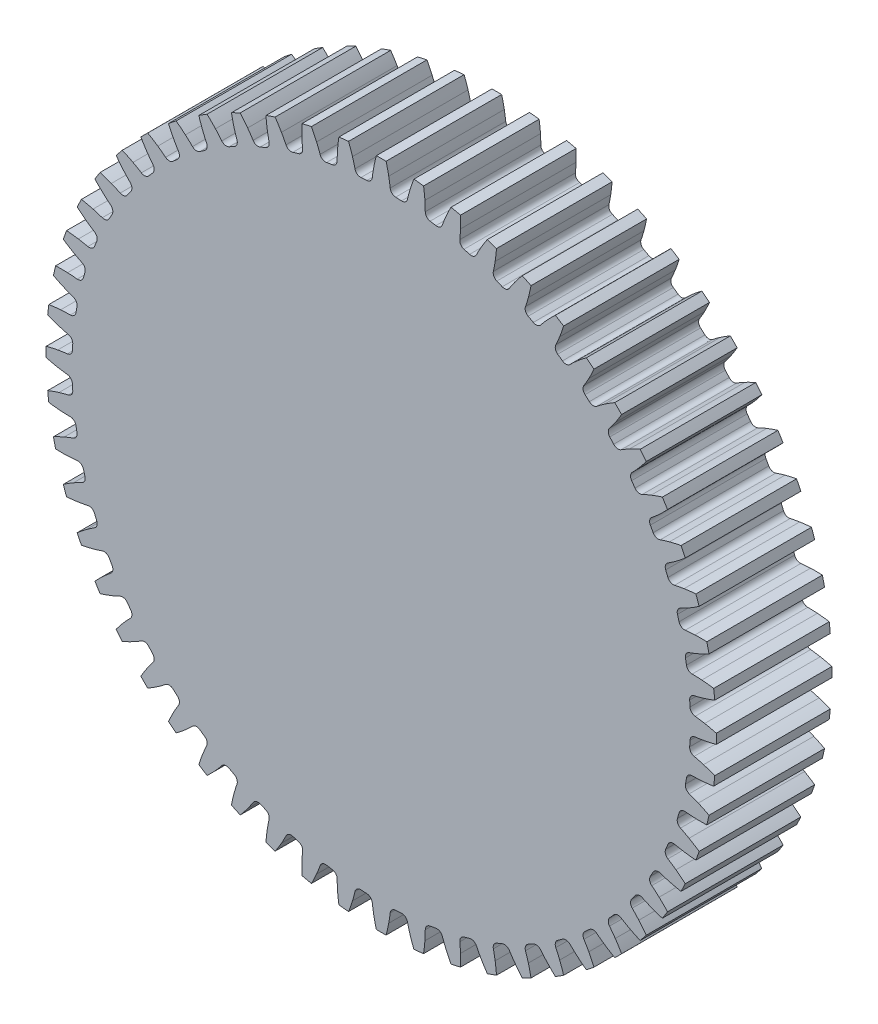
SolidWorks part; units mm, degrees
ref_plane "Front Plane" through (0, 0, 0) normal (0, 0, 1) x (1, 0, 0)
ref_plane "Top Plane" through (0, 0, 0) normal (0, 1, 0) x (1, 0, 0)
ref_plane "Right Plane" through (0, 0, 0) normal (1, 0, 0) x (0, 0, -1)
sketch "Sketch1" plane through (0, 0, 0) normal (0, 0, 1) x (1, 0, 0)
  line L0 (0, 145) -> (0, -145) construction
  circle A0 centre (0, 0) radius 140 construction
  circle A1 centre (0, 0) radius 145 construction
  arc A2 (-6.2373, 133.6045) -> (-8.7609, 133.4628) centre (0, 0) ccw
  arc A3 (-2.1, 144.9848) -> (2.1, 144.9848) centre (0, 0) cw
  arc A4 (2.1, 144.9848) -> (3.25, 139.9623) centre (-59.4844, 128.241) cw
  arc A5 (3.25, 139.9623) -> (3.8697, 135.8214) centre (-53.6651, 129.3283) cw
  arc A6 (3.8697, 135.8214) -> (6.2373, 133.6045) centre (6.3539, 136.1018) ccw
  arc A7 (-2.1, 144.9848) -> (-3.25, 139.9623) centre (59.4844, 128.241) ccw
  arc A8 (-3.25, 139.9623) -> (-3.8697, 135.8214) centre (53.6651, 129.3283) ccw
  arc A9 (-3.8697, 135.8214) -> (-6.2373, 133.6045) centre (-6.3539, 136.1018) cw
  arc A10 (11.3618, 135.4007) -> (8.7609, 133.4628) centre (8.9246, 135.9574) cw
  arc A11 (12.4412, 139.4461) -> (11.3618, 135.4007) centre (67.8078, 122.5065) ccw
  arc A12 (14.1464, 144.3083) -> (12.4412, 139.4461) centre (73.4688, 120.7745) ccw
  arc A13 (14.1464, 144.3083) -> (18.3199, 143.838) centre (0, 0) cw
  arc A14 (18.3199, 143.838) -> (18.9004, 138.7183) centre (-44.7519, 134.0948) cw
  arc A15 (18.9004, 138.7183) -> (19.0525, 134.5341) centre (-38.8475, 134.5237) cw
  arc A16 (19.0525, 134.5341) -> (21.1571, 132.0661) centre (21.5525, 134.5346) ccw
  arc A17 (26.4505, 133.2772) -> (23.6489, 131.6427) centre (24.0909, 134.1033) cw
  arc A18 (27.976, 137.1763) -> (26.4505, 133.2772) centre (81.0978, 114.1441) ccw
  arc A19 (30.2148, 141.817) -> (27.976, 137.1763) centre (86.5293, 111.7892) ccw
  arc A20 (30.2148, 141.817) -> (34.3095, 140.8824) centre (0, 0) cw
  arc A21 (34.3095, 140.8824) -> (34.3131, 135.7299) centre (-29.4567, 138.2622) cw
  arc A22 (34.3131, 135.7299) -> (33.9958, 131.555) centre (-23.5414, 138.0273) cw
  arc A23 (33.9958, 131.555) -> (35.8107, 128.8668) centre (36.4801, 131.2755) ccw
  arc A24 (41.2064, 129.4776) -> (38.2395, 128.1671) centre (38.9542, 130.5627) cw
  arc A25 (43.159, 133.1815) -> (41.2064, 129.4776) centre (93.368, 104.3463) ccw
  arc A26 (45.9033, 137.5423) -> (43.159, 133.1815) centre (98.5016, 101.3981) ccw
  arc A27 (45.9033, 137.5423) -> (49.8676, 136.1551) centre (0, 0) cw
  arc A28 (49.8676, 136.1551) -> (49.2942, 131.0346) centre (-13.791, 140.691) cw
  arc A29 (49.2942, 131.0346) -> (48.5115, 126.9215) centre (-7.9392, 139.7952) cw
  arc A30 (48.5115, 126.9215) -> (50.0141, 124.047) centre (50.9489, 126.3656) ccw
  arc A31 (55.4442, 124.0498) -> (52.3492, 123.0798) centre (53.3277, 125.3803) cw
  arc A32 (57.7992, 127.5118) -> (55.4442, 124.0498) centre (104.464, 93.2363) ccw
  arc A33 (61.0145, 131.5379) -> (57.7992, 127.5118) centre (109.2353, 89.7318) ccw
  arc A34 (61.0145, 131.5379) -> (64.7986, 129.7156) centre (0, 0) cw
  arc A35 (64.7986, 129.7156) -> (63.6555, 124.6915) centre (2.0481, 141.3504) cw
  arc A36 (63.6555, 124.6915) -> (62.4172, 120.6919) centre (7.7628, 139.8051) cw
  arc A37 (62.4172, 120.6919) -> (63.5884, 117.6672) centre (64.777, 119.8666) ccw
  arc A38 (68.9848, 117.0621) -> (65.8006, 116.4446) centre (67.0305, 118.6211) cw
  arc A39 (71.7126, 120.2385) -> (68.9848, 117.0621) centre (114.2463, 80.9538) ccw
  arc A40 (75.3584, 123.8794) -> (71.7126, 120.2385) centre (118.5952, 76.9371) ccw
  arc A41 (75.3584, 123.8794) -> (78.9147, 121.6449) centre (0, 0) cw
  arc A42 (78.9147, 121.6449) -> (77.2163, 116.7803) centre (17.8614, 140.2323) cw
  arc A43 (77.2163, 116.7803) -> (75.5379, 112.9445) centre (23.3672, 138.0569) cw
  arc A44 (75.5379, 112.9445) -> (76.3632, 109.8077) centre (77.7905, 111.8602) ccw
  arc A45 (81.6578, 108.6022) -> (78.4245, 108.3451) centre (79.8904, 110.3702) cw
  arc A46 (84.7241, 111.4533) -> (81.6578, 108.6022) centre (122.5919, 67.6533) ccw
  arc A47 (88.7547, 114.663) -> (84.7241, 111.4533) centre (126.4637, 63.1749) ccw
  arc A48 (88.7547, 114.663) -> (92.0384, 112.0443) centre (0, 0) cw
  arc A49 (92.0384, 112.0443) -> (89.806, 107.4006) centre (33.4502, 137.3507) cw
  arc A50 (89.806, 107.4006) -> (87.7087, 103.7767) centre (38.6778, 134.5725) cw
  arc A51 (87.7087, 103.7767) -> (88.1776, 100.5673) centre (89.8257, 102.4471) ccw
  arc A52 (93.304, 98.7765) -> (90.0622, 98.8831) centre (91.7456, 100.7314) cw
  arc A53 (96.6702, 101.2664) -> (93.304, 98.7765) centre (129.3958, 53.5019) ccw
  arc A54 (101.0348, 104.0047) -> (96.6702, 101.2664) centre (132.7419, 48.6182) ccw
  arc A55 (101.0348, 104.0047) -> (104.0047, 101.0348) centre (0, 0) cw
  arc A56 (104.0047, 101.0348) -> (101.2664, 96.6702) centre (48.6182, 132.7419) cw
  arc A57 (101.2664, 96.6702) -> (98.7765, 93.304) centre (53.5019, 129.3958) cw
  arc A58 (98.7765, 93.304) -> (98.8831, 90.0622) centre (100.7314, 91.7456) ccw
  arc A59 (103.7767, 87.7087) -> (100.5673, 88.1776) centre (102.4471, 89.8257) cw
  arc A60 (107.4006, 89.806) -> (103.7767, 87.7087) centre (134.5725, 38.6778) ccw
  arc A61 (112.0443, 92.0384) -> (107.4006, 89.806) centre (137.3507, 33.4502) ccw
  arc A62 (112.0443, 92.0384) -> (114.663, 88.7547) centre (0, 0) cw
  arc A63 (114.663, 88.7547) -> (111.4533, 84.7241) centre (63.1749, 126.4637) cw
  arc A64 (111.4533, 84.7241) -> (108.6022, 81.6578) centre (67.6533, 122.5919) cw
  arc A65 (108.6022, 81.6578) -> (108.3451, 78.4245) centre (110.3702, 79.8904) ccw
  arc A66 (112.9445, 75.5379) -> (109.8077, 76.3632) centre (111.8602, 77.7905) cw
  arc A67 (116.7803, 77.2163) -> (112.9445, 75.5379) centre (138.0569, 23.3672) ccw
  arc A68 (121.6449, 78.9147) -> (116.7803, 77.2163) centre (140.2323, 17.8614) ccw
  arc A69 (121.6449, 78.9147) -> (123.8794, 75.3584) centre (0, 0) cw
  arc A70 (123.8794, 75.3584) -> (120.2385, 71.7126) centre (76.9371, 118.5952) cw
  arc A71 (120.2385, 71.7126) -> (117.0621, 68.9848) centre (80.9538, 114.2463) cw
  arc A72 (117.0621, 68.9848) -> (116.4446, 65.8006) centre (118.6211, 67.0305) ccw
  arc A73 (120.6919, 62.4172) -> (117.6672, 63.5884) centre (119.8666, 64.777) cw
  arc A74 (124.6915, 63.6555) -> (120.6919, 62.4172) centre (139.8051, 7.7628) ccw
  arc A75 (129.7156, 64.7986) -> (124.6915, 63.6555) centre (141.3504, 2.0481) ccw
  arc A76 (129.7156, 64.7986) -> (131.5379, 61.0145) centre (0, 0) cw
  arc A77 (131.5379, 61.0145) -> (127.5118, 57.7992) centre (89.7318, 109.2353) cw
  arc A78 (127.5118, 57.7992) -> (124.0498, 55.4442) centre (93.2363, 104.464) cw
  arc A79 (124.0498, 55.4442) -> (123.0798, 52.3492) centre (125.3803, 53.3277) ccw
  arc A80 (126.9215, 48.5115) -> (124.047, 50.0141) centre (126.3656, 50.9489) cw
  arc A81 (131.0346, 49.2942) -> (126.9215, 48.5115) centre (139.7952, -7.9392) ccw
  arc A82 (136.1551, 49.8676) -> (131.0346, 49.2942) centre (140.691, -13.791) ccw
  arc A83 (136.1551, 49.8676) -> (137.5423, 45.9033) centre (0, 0) cw
  arc A84 (137.5423, 45.9033) -> (133.1815, 43.159) centre (101.3981, 98.5016) cw
  arc A85 (133.1815, 43.159) -> (129.4776, 41.2064) centre (104.3463, 93.368) cw
  arc A86 (129.4776, 41.2064) -> (128.1671, 38.2395) centre (130.5627, 38.9542) ccw
  arc A87 (131.555, 33.9958) -> (128.8668, 35.8107) centre (131.2755, 36.4801) cw
  arc A88 (135.7299, 34.3131) -> (131.555, 33.9958) centre (138.0273, -23.5414) ccw
  arc A89 (140.8824, 34.3095) -> (135.7299, 34.3131) centre (138.2622, -29.4567) ccw
  arc A90 (140.8824, 34.3095) -> (141.817, 30.2148) centre (0, 0) cw
  arc A91 (141.817, 30.2148) -> (137.1763, 27.976) centre (111.7892, 86.5293) cw
  arc A92 (137.1763, 27.976) -> (133.2772, 26.4505) centre (114.1441, 81.0978) cw
  arc A93 (133.2772, 26.4505) -> (131.6427, 23.6489) centre (134.1033, 24.0909) ccw
  arc A94 (134.5341, 19.0525) -> (132.0661, 21.1571) centre (134.5346, 21.5525) cw
  arc A95 (138.7183, 18.9004) -> (134.5341, 19.0525) centre (134.5237, -38.8475) ccw
  arc A96 (143.838, 18.3199) -> (138.7183, 18.9004) centre (134.0948, -44.7519) ccw
  arc A97 (143.838, 18.3199) -> (144.3083, 14.1464) centre (0, 0) cw
  arc A98 (144.3083, 14.1464) -> (139.4461, 12.4412) centre (120.7745, 73.4688) cw
  arc A99 (139.4461, 12.4412) -> (135.4007, 11.3618) centre (122.5065, 67.8078) cw
  arc A100 (135.4007, 11.3618) -> (133.4628, 8.7609) centre (135.9574, 8.9246) ccw
  arc A101 (135.8214, 3.8697) -> (133.6045, 6.2373) centre (136.1018, 6.3539) cw
  arc A102 (139.9623, 3.25) -> (135.8214, 3.8697) centre (129.3283, -53.6651) ccw
  arc A103 (144.9848, 2.1) -> (139.9623, 3.25) centre (128.241, -59.4844) ccw
  arc A104 (144.9848, 2.1) -> (144.9848, -2.1) centre (0, 0) cw
  arc A105 (144.9848, -2.1) -> (139.9623, -3.25) centre (128.241, 59.4844) cw
  arc A106 (139.9623, -3.25) -> (135.8214, -3.8697) centre (129.3283, 53.6651) cw
  arc A107 (135.8214, -3.8697) -> (133.6045, -6.2373) centre (136.1018, -6.3539) ccw
  arc A108 (135.4007, -11.3618) -> (133.4628, -8.7609) centre (135.9574, -8.9246) cw
  arc A109 (139.4461, -12.4412) -> (135.4007, -11.3618) centre (122.5065, -67.8078) ccw
  arc A110 (144.3083, -14.1464) -> (139.4461, -12.4412) centre (120.7745, -73.4688) ccw
  arc A111 (144.3083, -14.1464) -> (143.838, -18.3199) centre (0, 0) cw
  arc A112 (143.838, -18.3199) -> (138.7183, -18.9004) centre (134.0948, 44.7519) cw
  arc A113 (138.7183, -18.9004) -> (134.5341, -19.0525) centre (134.5237, 38.8475) cw
  arc A114 (134.5341, -19.0525) -> (132.0661, -21.1571) centre (134.5346, -21.5525) ccw
  arc A115 (133.2772, -26.4505) -> (131.6427, -23.6489) centre (134.1033, -24.0909) cw
  arc A116 (137.1763, -27.976) -> (133.2772, -26.4505) centre (114.1441, -81.0978) ccw
  arc A117 (141.817, -30.2148) -> (137.1763, -27.976) centre (111.7892, -86.5293) ccw
  arc A118 (141.817, -30.2148) -> (140.8824, -34.3095) centre (0, 0) cw
  arc A119 (140.8824, -34.3095) -> (135.7299, -34.3131) centre (138.2622, 29.4567) cw
  arc A120 (135.7299, -34.3131) -> (131.555, -33.9958) centre (138.0273, 23.5414) cw
  arc A121 (131.555, -33.9958) -> (128.8668, -35.8107) centre (131.2755, -36.4801) ccw
  arc A122 (129.4776, -41.2064) -> (128.1671, -38.2395) centre (130.5627, -38.9542) cw
  arc A123 (133.1815, -43.159) -> (129.4776, -41.2064) centre (104.3463, -93.368) ccw
  arc A124 (137.5423, -45.9033) -> (133.1815, -43.159) centre (101.3981, -98.5016) ccw
  arc A125 (137.5423, -45.9033) -> (136.1551, -49.8676) centre (0, 0) cw
  arc A126 (136.1551, -49.8676) -> (131.0346, -49.2942) centre (140.691, 13.791) cw
  arc A127 (131.0346, -49.2942) -> (126.9215, -48.5115) centre (139.7952, 7.9392) cw
  arc A128 (126.9215, -48.5115) -> (124.047, -50.0141) centre (126.3656, -50.9489) ccw
  arc A129 (124.0498, -55.4442) -> (123.0798, -52.3492) centre (125.3803, -53.3277) cw
  arc A130 (127.5118, -57.7992) -> (124.0498, -55.4442) centre (93.2363, -104.464) ccw
  arc A131 (131.5379, -61.0145) -> (127.5118, -57.7992) centre (89.7318, -109.2353) ccw
  arc A132 (131.5379, -61.0145) -> (129.7156, -64.7986) centre (0, 0) cw
  arc A133 (129.7156, -64.7986) -> (124.6915, -63.6555) centre (141.3504, -2.0481) cw
  arc A134 (124.6915, -63.6555) -> (120.6919, -62.4172) centre (139.8051, -7.7628) cw
  arc A135 (120.6919, -62.4172) -> (117.6672, -63.5884) centre (119.8666, -64.777) ccw
  arc A136 (117.0621, -68.9848) -> (116.4446, -65.8006) centre (118.6211, -67.0305) cw
  arc A137 (120.2385, -71.7126) -> (117.0621, -68.9848) centre (80.9538, -114.2463) ccw
  arc A138 (123.8794, -75.3584) -> (120.2385, -71.7126) centre (76.9371, -118.5952) ccw
  arc A139 (123.8794, -75.3584) -> (121.6449, -78.9147) centre (0, 0) cw
  arc A140 (121.6449, -78.9147) -> (116.7803, -77.2163) centre (140.2323, -17.8614) cw
  arc A141 (116.7803, -77.2163) -> (112.9445, -75.5379) centre (138.0569, -23.3672) cw
  arc A142 (112.9445, -75.5379) -> (109.8077, -76.3632) centre (111.8602, -77.7905) ccw
  arc A143 (108.6022, -81.6578) -> (108.3451, -78.4245) centre (110.3702, -79.8904) cw
  arc A144 (111.4533, -84.7241) -> (108.6022, -81.6578) centre (67.6533, -122.5919) ccw
  arc A145 (114.663, -88.7547) -> (111.4533, -84.7241) centre (63.1749, -126.4637) ccw
  arc A146 (114.663, -88.7547) -> (112.0443, -92.0384) centre (0, 0) cw
  arc A147 (112.0443, -92.0384) -> (107.4006, -89.806) centre (137.3507, -33.4502) cw
  arc A148 (107.4006, -89.806) -> (103.7767, -87.7087) centre (134.5725, -38.6778) cw
  arc A149 (103.7767, -87.7087) -> (100.5673, -88.1776) centre (102.4471, -89.8257) ccw
  arc A150 (98.7765, -93.304) -> (98.8831, -90.0622) centre (100.7314, -91.7456) cw
  arc A151 (101.2664, -96.6702) -> (98.7765, -93.304) centre (53.5019, -129.3958) ccw
  arc A152 (104.0047, -101.0348) -> (101.2664, -96.6702) centre (48.6182, -132.7419) ccw
  arc A153 (104.0047, -101.0348) -> (101.0348, -104.0047) centre (0, 0) cw
  arc A154 (101.0348, -104.0047) -> (96.6702, -101.2664) centre (132.7419, -48.6182) cw
  arc A155 (96.6702, -101.2664) -> (93.304, -98.7765) centre (129.3958, -53.5019) cw
  arc A156 (93.304, -98.7765) -> (90.0622, -98.8831) centre (91.7456, -100.7314) ccw
  arc A157 (87.7087, -103.7767) -> (88.1776, -100.5673) centre (89.8257, -102.4471) cw
  arc A158 (89.806, -107.4006) -> (87.7087, -103.7767) centre (38.6778, -134.5725) ccw
  arc A159 (92.0384, -112.0443) -> (89.806, -107.4006) centre (33.4502, -137.3507) ccw
  arc A160 (92.0384, -112.0443) -> (88.7547, -114.663) centre (0, 0) cw
  arc A161 (88.7547, -114.663) -> (84.7241, -111.4533) centre (126.4637, -63.1749) cw
  arc A162 (84.7241, -111.4533) -> (81.6578, -108.6022) centre (122.5919, -67.6533) cw
  arc A163 (81.6578, -108.6022) -> (78.4245, -108.3451) centre (79.8904, -110.3702) ccw
  arc A164 (75.5379, -112.9445) -> (76.3632, -109.8077) centre (77.7905, -111.8602) cw
  arc A165 (77.2163, -116.7803) -> (75.5379, -112.9445) centre (23.3672, -138.0569) ccw
  arc A166 (78.9147, -121.6449) -> (77.2163, -116.7803) centre (17.8614, -140.2323) ccw
  arc A167 (78.9147, -121.6449) -> (75.3584, -123.8794) centre (0, 0) cw
  arc A168 (75.3584, -123.8794) -> (71.7126, -120.2385) centre (118.5952, -76.9371) cw
  arc A169 (71.7126, -120.2385) -> (68.9848, -117.0621) centre (114.2463, -80.9538) cw
  arc A170 (68.9848, -117.0621) -> (65.8006, -116.4446) centre (67.0305, -118.6211) ccw
  arc A171 (62.4172, -120.6919) -> (63.5884, -117.6672) centre (64.777, -119.8666) cw
  arc A172 (63.6555, -124.6915) -> (62.4172, -120.6919) centre (7.7628, -139.8051) ccw
  arc A173 (64.7986, -129.7156) -> (63.6555, -124.6915) centre (2.0481, -141.3504) ccw
  arc A174 (64.7986, -129.7156) -> (61.0145, -131.5379) centre (0, 0) cw
  arc A175 (61.0145, -131.5379) -> (57.7992, -127.5118) centre (109.2353, -89.7318) cw
  arc A176 (57.7992, -127.5118) -> (55.4442, -124.0498) centre (104.464, -93.2363) cw
  arc A177 (55.4442, -124.0498) -> (52.3492, -123.0798) centre (53.3277, -125.3803) ccw
  arc A178 (48.5115, -126.9215) -> (50.0141, -124.047) centre (50.9489, -126.3656) cw
  arc A179 (49.2942, -131.0346) -> (48.5115, -126.9215) centre (-7.9392, -139.7952) ccw
  arc A180 (49.8676, -136.1551) -> (49.2942, -131.0346) centre (-13.791, -140.691) ccw
  arc A181 (49.8676, -136.1551) -> (45.9033, -137.5423) centre (0, 0) cw
  arc A182 (45.9033, -137.5423) -> (43.159, -133.1815) centre (98.5016, -101.3981) cw
  arc A183 (43.159, -133.1815) -> (41.2064, -129.4776) centre (93.368, -104.3463) cw
  arc A184 (41.2064, -129.4776) -> (38.2395, -128.1671) centre (38.9542, -130.5627) ccw
  arc A185 (33.9958, -131.555) -> (35.8107, -128.8668) centre (36.4801, -131.2755) cw
  arc A186 (34.3131, -135.7299) -> (33.9958, -131.555) centre (-23.5414, -138.0273) ccw
  arc A187 (34.3095, -140.8824) -> (34.3131, -135.7299) centre (-29.4567, -138.2622) ccw
  arc A188 (34.3095, -140.8824) -> (30.2148, -141.817) centre (0, 0) cw
  arc A189 (30.2148, -141.817) -> (27.976, -137.1763) centre (86.5293, -111.7892) cw
  arc A190 (27.976, -137.1763) -> (26.4505, -133.2772) centre (81.0978, -114.1441) cw
  arc A191 (26.4505, -133.2772) -> (23.6489, -131.6427) centre (24.0909, -134.1033) ccw
  arc A192 (19.0525, -134.5341) -> (21.1571, -132.0661) centre (21.5525, -134.5346) cw
  arc A193 (18.9004, -138.7183) -> (19.0525, -134.5341) centre (-38.8475, -134.5237) ccw
  arc A194 (18.3199, -143.838) -> (18.9004, -138.7183) centre (-44.7519, -134.0948) ccw
  arc A195 (18.3199, -143.838) -> (14.1464, -144.3083) centre (0, 0) cw
  arc A196 (14.1464, -144.3083) -> (12.4412, -139.4461) centre (73.4688, -120.7745) cw
  arc A197 (12.4412, -139.4461) -> (11.3618, -135.4007) centre (67.8078, -122.5065) cw
  arc A198 (11.3618, -135.4007) -> (8.7609, -133.4628) centre (8.9246, -135.9574) ccw
  arc A199 (3.8697, -135.8214) -> (6.2373, -133.6045) centre (6.3539, -136.1018) cw
  arc A200 (3.25, -139.9623) -> (3.8697, -135.8214) centre (-53.6651, -129.3283) ccw
  arc A201 (2.1, -144.9848) -> (3.25, -139.9623) centre (-59.4844, -128.241) ccw
  arc A202 (2.1, -144.9848) -> (-2.1, -144.9848) centre (0, 0) cw
  arc A203 (-2.1, -144.9848) -> (-3.25, -139.9623) centre (59.4844, -128.241) cw
  arc A204 (-3.25, -139.9623) -> (-3.8697, -135.8214) centre (53.6651, -129.3283) cw
  arc A205 (-3.8697, -135.8214) -> (-6.2373, -133.6045) centre (-6.3539, -136.1018) ccw
  arc A206 (-11.3618, -135.4007) -> (-8.7609, -133.4628) centre (-8.9246, -135.9574) cw
  arc A207 (-12.4412, -139.4461) -> (-11.3618, -135.4007) centre (-67.8078, -122.5065) ccw
  arc A208 (-14.1464, -144.3083) -> (-12.4412, -139.4461) centre (-73.4688, -120.7745) ccw
  arc A209 (-14.1464, -144.3083) -> (-18.3199, -143.838) centre (0, 0) cw
  arc A210 (-18.3199, -143.838) -> (-18.9004, -138.7183) centre (44.7519, -134.0948) cw
  arc A211 (-18.9004, -138.7183) -> (-19.0525, -134.5341) centre (38.8475, -134.5237) cw
  arc A212 (-19.0525, -134.5341) -> (-21.1571, -132.0661) centre (-21.5525, -134.5346) ccw
  arc A213 (-26.4505, -133.2772) -> (-23.6489, -131.6427) centre (-24.0909, -134.1033) cw
  arc A214 (-27.976, -137.1763) -> (-26.4505, -133.2772) centre (-81.0978, -114.1441) ccw
  arc A215 (-30.2148, -141.817) -> (-27.976, -137.1763) centre (-86.5293, -111.7892) ccw
  arc A216 (-30.2148, -141.817) -> (-34.3095, -140.8824) centre (0, 0) cw
  arc A217 (-34.3095, -140.8824) -> (-34.3131, -135.7299) centre (29.4567, -138.2622) cw
  arc A218 (-34.3131, -135.7299) -> (-33.9958, -131.555) centre (23.5414, -138.0273) cw
  arc A219 (-33.9958, -131.555) -> (-35.8107, -128.8668) centre (-36.4801, -131.2755) ccw
  arc A220 (-41.2064, -129.4776) -> (-38.2395, -128.1671) centre (-38.9542, -130.5627) cw
  arc A221 (-43.159, -133.1815) -> (-41.2064, -129.4776) centre (-93.368, -104.3463) ccw
  arc A222 (-45.9033, -137.5423) -> (-43.159, -133.1815) centre (-98.5016, -101.3981) ccw
  arc A223 (-45.9033, -137.5423) -> (-49.8676, -136.1551) centre (0, 0) cw
  arc A224 (-49.8676, -136.1551) -> (-49.2942, -131.0346) centre (13.791, -140.691) cw
  arc A225 (-49.2942, -131.0346) -> (-48.5115, -126.9215) centre (7.9392, -139.7952) cw
  arc A226 (-48.5115, -126.9215) -> (-50.0141, -124.047) centre (-50.9489, -126.3656) ccw
  arc A227 (-55.4442, -124.0498) -> (-52.3492, -123.0798) centre (-53.3277, -125.3803) cw
  arc A228 (-57.7992, -127.5118) -> (-55.4442, -124.0498) centre (-104.464, -93.2363) ccw
  arc A229 (-61.0145, -131.5379) -> (-57.7992, -127.5118) centre (-109.2353, -89.7318) ccw
  arc A230 (-61.0145, -131.5379) -> (-64.7986, -129.7156) centre (0, 0) cw
  arc A231 (-64.7986, -129.7156) -> (-63.6555, -124.6915) centre (-2.0481, -141.3504) cw
  arc A232 (-63.6555, -124.6915) -> (-62.4172, -120.6919) centre (-7.7628, -139.8051) cw
  arc A233 (-62.4172, -120.6919) -> (-63.5884, -117.6672) centre (-64.777, -119.8666) ccw
  arc A234 (-68.9848, -117.0621) -> (-65.8006, -116.4446) centre (-67.0305, -118.6211) cw
  arc A235 (-71.7126, -120.2385) -> (-68.9848, -117.0621) centre (-114.2463, -80.9538) ccw
  arc A236 (-75.3584, -123.8794) -> (-71.7126, -120.2385) centre (-118.5952, -76.9371) ccw
  arc A237 (-75.3584, -123.8794) -> (-78.9147, -121.6449) centre (0, 0) cw
  arc A238 (-78.9147, -121.6449) -> (-77.2163, -116.7803) centre (-17.8614, -140.2323) cw
  arc A239 (-77.2163, -116.7803) -> (-75.5379, -112.9445) centre (-23.3672, -138.0569) cw
  arc A240 (-75.5379, -112.9445) -> (-76.3632, -109.8077) centre (-77.7905, -111.8602) ccw
  arc A241 (-81.6578, -108.6022) -> (-78.4245, -108.3451) centre (-79.8904, -110.3702) cw
  arc A242 (-84.7241, -111.4533) -> (-81.6578, -108.6022) centre (-122.5919, -67.6533) ccw
  arc A243 (-88.7547, -114.663) -> (-84.7241, -111.4533) centre (-126.4637, -63.1749) ccw
  arc A244 (-88.7547, -114.663) -> (-92.0384, -112.0443) centre (0, 0) cw
  arc A245 (-92.0384, -112.0443) -> (-89.806, -107.4006) centre (-33.4502, -137.3507) cw
  arc A246 (-89.806, -107.4006) -> (-87.7087, -103.7767) centre (-38.6778, -134.5725) cw
  arc A247 (-87.7087, -103.7767) -> (-88.1776, -100.5673) centre (-89.8257, -102.4471) ccw
  arc A248 (-93.304, -98.7765) -> (-90.0622, -98.8831) centre (-91.7456, -100.7314) cw
  arc A249 (-96.6702, -101.2664) -> (-93.304, -98.7765) centre (-129.3958, -53.5019) ccw
  arc A250 (-101.0348, -104.0047) -> (-96.6702, -101.2664) centre (-132.7419, -48.6182) ccw
  arc A251 (-101.0348, -104.0047) -> (-104.0047, -101.0348) centre (0, 0) cw
  arc A252 (-104.0047, -101.0348) -> (-101.2664, -96.6702) centre (-48.6182, -132.7419) cw
  arc A253 (-101.2664, -96.6702) -> (-98.7765, -93.304) centre (-53.5019, -129.3958) cw
  arc A254 (-98.7765, -93.304) -> (-98.8831, -90.0622) centre (-100.7314, -91.7456) ccw
  arc A255 (-103.7767, -87.7087) -> (-100.5673, -88.1776) centre (-102.4471, -89.8257) cw
  arc A256 (-107.4006, -89.806) -> (-103.7767, -87.7087) centre (-134.5725, -38.6778) ccw
  arc A257 (-112.0443, -92.0384) -> (-107.4006, -89.806) centre (-137.3507, -33.4502) ccw
  arc A258 (-112.0443, -92.0384) -> (-114.663, -88.7547) centre (0, 0) cw
  arc A259 (-114.663, -88.7547) -> (-111.4533, -84.7241) centre (-63.1749, -126.4637) cw
  arc A260 (-111.4533, -84.7241) -> (-108.6022, -81.6578) centre (-67.6533, -122.5919) cw
  arc A261 (-108.6022, -81.6578) -> (-108.3451, -78.4245) centre (-110.3702, -79.8904) ccw
  arc A262 (-112.9445, -75.5379) -> (-109.8077, -76.3632) centre (-111.8602, -77.7905) cw
  arc A263 (-116.7803, -77.2163) -> (-112.9445, -75.5379) centre (-138.0569, -23.3672) ccw
  arc A264 (-121.6449, -78.9147) -> (-116.7803, -77.2163) centre (-140.2323, -17.8614) ccw
  arc A265 (-121.6449, -78.9147) -> (-123.8794, -75.3584) centre (0, 0) cw
  arc A266 (-123.8794, -75.3584) -> (-120.2385, -71.7126) centre (-76.9371, -118.5952) cw
  arc A267 (-120.2385, -71.7126) -> (-117.0621, -68.9848) centre (-80.9538, -114.2463) cw
  arc A268 (-117.0621, -68.9848) -> (-116.4446, -65.8006) centre (-118.6211, -67.0305) ccw
  arc A269 (-120.6919, -62.4172) -> (-117.6672, -63.5884) centre (-119.8666, -64.777) cw
  arc A270 (-124.6915, -63.6555) -> (-120.6919, -62.4172) centre (-139.8051, -7.7628) ccw
  arc A271 (-129.7156, -64.7986) -> (-124.6915, -63.6555) centre (-141.3504, -2.0481) ccw
  arc A272 (-129.7156, -64.7986) -> (-131.5379, -61.0145) centre (0, 0) cw
  arc A273 (-131.5379, -61.0145) -> (-127.5118, -57.7992) centre (-89.7318, -109.2353) cw
  arc A274 (-127.5118, -57.7992) -> (-124.0498, -55.4442) centre (-93.2363, -104.464) cw
  arc A275 (-124.0498, -55.4442) -> (-123.0798, -52.3492) centre (-125.3803, -53.3277) ccw
  arc A276 (-126.9215, -48.5115) -> (-124.047, -50.0141) centre (-126.3656, -50.9489) cw
  arc A277 (-131.0346, -49.2942) -> (-126.9215, -48.5115) centre (-139.7952, 7.9392) ccw
  arc A278 (-136.1551, -49.8676) -> (-131.0346, -49.2942) centre (-140.691, 13.791) ccw
  arc A279 (-136.1551, -49.8676) -> (-137.5423, -45.9033) centre (0, 0) cw
  arc A280 (-137.5423, -45.9033) -> (-133.1815, -43.159) centre (-101.3981, -98.5016) cw
  arc A281 (-133.1815, -43.159) -> (-129.4776, -41.2064) centre (-104.3463, -93.368) cw
  arc A282 (-129.4776, -41.2064) -> (-128.1671, -38.2395) centre (-130.5627, -38.9542) ccw
  arc A283 (-131.555, -33.9958) -> (-128.8668, -35.8107) centre (-131.2755, -36.4801) cw
  arc A284 (-135.7299, -34.3131) -> (-131.555, -33.9958) centre (-138.0273, 23.5414) ccw
  arc A285 (-140.8824, -34.3095) -> (-135.7299, -34.3131) centre (-138.2622, 29.4567) ccw
  arc A286 (-140.8824, -34.3095) -> (-141.817, -30.2148) centre (0, 0) cw
  arc A287 (-141.817, -30.2148) -> (-137.1763, -27.976) centre (-111.7892, -86.5293) cw
  arc A288 (-137.1763, -27.976) -> (-133.2772, -26.4505) centre (-114.1441, -81.0978) cw
  arc A289 (-133.2772, -26.4505) -> (-131.6427, -23.6489) centre (-134.1033, -24.0909) ccw
  arc A290 (-134.5341, -19.0525) -> (-132.0661, -21.1571) centre (-134.5346, -21.5525) cw
  arc A291 (-138.7183, -18.9004) -> (-134.5341, -19.0525) centre (-134.5237, 38.8475) ccw
  arc A292 (-143.838, -18.3199) -> (-138.7183, -18.9004) centre (-134.0948, 44.7519) ccw
  arc A293 (-143.838, -18.3199) -> (-144.3083, -14.1464) centre (0, 0) cw
  arc A294 (-144.3083, -14.1464) -> (-139.4461, -12.4412) centre (-120.7745, -73.4688) cw
  arc A295 (-139.4461, -12.4412) -> (-135.4007, -11.3618) centre (-122.5065, -67.8078) cw
  arc A296 (-135.4007, -11.3618) -> (-133.4628, -8.7609) centre (-135.9574, -8.9246) ccw
  arc A297 (-135.8214, -3.8697) -> (-133.6045, -6.2373) centre (-136.1018, -6.3539) cw
  arc A298 (-139.9623, -3.25) -> (-135.8214, -3.8697) centre (-129.3283, 53.6651) ccw
  arc A299 (-144.9848, -2.1) -> (-139.9623, -3.25) centre (-128.241, 59.4844) ccw
  arc A300 (-144.9848, -2.1) -> (-144.9848, 2.1) centre (0, 0) cw
  arc A301 (-144.9848, 2.1) -> (-139.9623, 3.25) centre (-128.241, -59.4844) cw
  arc A302 (-139.9623, 3.25) -> (-135.8214, 3.8697) centre (-129.3283, -53.6651) cw
  arc A303 (-135.8214, 3.8697) -> (-133.6045, 6.2373) centre (-136.1018, 6.3539) ccw
  arc A304 (-135.4007, 11.3618) -> (-133.4628, 8.7609) centre (-135.9574, 8.9246) cw
  arc A305 (-139.4461, 12.4412) -> (-135.4007, 11.3618) centre (-122.5065, 67.8078) ccw
  arc A306 (-144.3083, 14.1464) -> (-139.4461, 12.4412) centre (-120.7745, 73.4688) ccw
  arc A307 (-144.3083, 14.1464) -> (-143.838, 18.3199) centre (0, 0) cw
  arc A308 (-143.838, 18.3199) -> (-138.7183, 18.9004) centre (-134.0948, -44.7519) cw
  arc A309 (-138.7183, 18.9004) -> (-134.5341, 19.0525) centre (-134.5237, -38.8475) cw
  arc A310 (-134.5341, 19.0525) -> (-132.0661, 21.1571) centre (-134.5346, 21.5525) ccw
  arc A311 (-133.2772, 26.4505) -> (-131.6427, 23.6489) centre (-134.1033, 24.0909) cw
  arc A312 (-137.1763, 27.976) -> (-133.2772, 26.4505) centre (-114.1441, 81.0978) ccw
  arc A313 (-141.817, 30.2148) -> (-137.1763, 27.976) centre (-111.7892, 86.5293) ccw
  arc A314 (-141.817, 30.2148) -> (-140.8824, 34.3095) centre (0, 0) cw
  arc A315 (-140.8824, 34.3095) -> (-135.7299, 34.3131) centre (-138.2622, -29.4567) cw
  arc A316 (-135.7299, 34.3131) -> (-131.555, 33.9958) centre (-138.0273, -23.5414) cw
  arc A317 (-131.555, 33.9958) -> (-128.8668, 35.8107) centre (-131.2755, 36.4801) ccw
  arc A318 (-129.4776, 41.2064) -> (-128.1671, 38.2395) centre (-130.5627, 38.9542) cw
  arc A319 (-133.1815, 43.159) -> (-129.4776, 41.2064) centre (-104.3463, 93.368) ccw
  arc A320 (-137.5423, 45.9033) -> (-133.1815, 43.159) centre (-101.3981, 98.5016) ccw
  arc A321 (-137.5423, 45.9033) -> (-136.1551, 49.8676) centre (0, 0) cw
  arc A322 (-136.1551, 49.8676) -> (-131.0346, 49.2942) centre (-140.691, -13.791) cw
  arc A323 (-131.0346, 49.2942) -> (-126.9215, 48.5115) centre (-139.7952, -7.9392) cw
  arc A324 (-126.9215, 48.5115) -> (-124.047, 50.0141) centre (-126.3656, 50.9489) ccw
  arc A325 (-124.0498, 55.4442) -> (-123.0798, 52.3492) centre (-125.3803, 53.3277) cw
  arc A326 (-127.5118, 57.7992) -> (-124.0498, 55.4442) centre (-93.2363, 104.464) ccw
  arc A327 (-131.5379, 61.0145) -> (-127.5118, 57.7992) centre (-89.7318, 109.2353) ccw
  arc A328 (-131.5379, 61.0145) -> (-129.7156, 64.7986) centre (0, 0) cw
  arc A329 (-129.7156, 64.7986) -> (-124.6915, 63.6555) centre (-141.3504, 2.0481) cw
  arc A330 (-124.6915, 63.6555) -> (-120.6919, 62.4172) centre (-139.8051, 7.7628) cw
  arc A331 (-120.6919, 62.4172) -> (-117.6672, 63.5884) centre (-119.8666, 64.777) ccw
  arc A332 (-117.0621, 68.9848) -> (-116.4446, 65.8006) centre (-118.6211, 67.0305) cw
  arc A333 (-120.2385, 71.7126) -> (-117.0621, 68.9848) centre (-80.9538, 114.2463) ccw
  arc A334 (-123.8794, 75.3584) -> (-120.2385, 71.7126) centre (-76.9371, 118.5952) ccw
  arc A335 (-123.8794, 75.3584) -> (-121.6449, 78.9147) centre (0, 0) cw
  arc A336 (-121.6449, 78.9147) -> (-116.7803, 77.2163) centre (-140.2323, 17.8614) cw
  arc A337 (-116.7803, 77.2163) -> (-112.9445, 75.5379) centre (-138.0569, 23.3672) cw
  arc A338 (-112.9445, 75.5379) -> (-109.8077, 76.3632) centre (-111.8602, 77.7905) ccw
  arc A339 (-108.6022, 81.6578) -> (-108.3451, 78.4245) centre (-110.3702, 79.8904) cw
  arc A340 (-111.4533, 84.7241) -> (-108.6022, 81.6578) centre (-67.6533, 122.5919) ccw
  arc A341 (-114.663, 88.7547) -> (-111.4533, 84.7241) centre (-63.1749, 126.4637) ccw
  arc A342 (-114.663, 88.7547) -> (-112.0443, 92.0384) centre (0, 0) cw
  arc A343 (-112.0443, 92.0384) -> (-107.4006, 89.806) centre (-137.3507, 33.4502) cw
  arc A344 (-107.4006, 89.806) -> (-103.7767, 87.7087) centre (-134.5725, 38.6778) cw
  arc A345 (-103.7767, 87.7087) -> (-100.5673, 88.1776) centre (-102.4471, 89.8257) ccw
  arc A346 (-98.7765, 93.304) -> (-98.8831, 90.0622) centre (-100.7314, 91.7456) cw
  arc A347 (-101.2664, 96.6702) -> (-98.7765, 93.304) centre (-53.5019, 129.3958) ccw
  arc A348 (-104.0047, 101.0348) -> (-101.2664, 96.6702) centre (-48.6182, 132.7419) ccw
  arc A349 (-104.0047, 101.0348) -> (-101.0348, 104.0047) centre (0, 0) cw
  arc A350 (-101.0348, 104.0047) -> (-96.6702, 101.2664) centre (-132.7419, 48.6182) cw
  arc A351 (-96.6702, 101.2664) -> (-93.304, 98.7765) centre (-129.3958, 53.5019) cw
  arc A352 (-93.304, 98.7765) -> (-90.0622, 98.8831) centre (-91.7456, 100.7314) ccw
  arc A353 (-87.7087, 103.7767) -> (-88.1776, 100.5673) centre (-89.8257, 102.4471) cw
  arc A354 (-89.806, 107.4006) -> (-87.7087, 103.7767) centre (-38.6778, 134.5725) ccw
  arc A355 (-92.0384, 112.0443) -> (-89.806, 107.4006) centre (-33.4502, 137.3507) ccw
  arc A356 (-92.0384, 112.0443) -> (-88.7547, 114.663) centre (0, 0) cw
  arc A357 (-88.7547, 114.663) -> (-84.7241, 111.4533) centre (-126.4637, 63.1749) cw
  arc A358 (-84.7241, 111.4533) -> (-81.6578, 108.6022) centre (-122.5919, 67.6533) cw
  arc A359 (-81.6578, 108.6022) -> (-78.4245, 108.3451) centre (-79.8904, 110.3702) ccw
  arc A360 (-75.5379, 112.9445) -> (-76.3632, 109.8077) centre (-77.7905, 111.8602) cw
  arc A361 (-77.2163, 116.7803) -> (-75.5379, 112.9445) centre (-23.3672, 138.0569) ccw
  arc A362 (-78.9147, 121.6449) -> (-77.2163, 116.7803) centre (-17.8614, 140.2323) ccw
  arc A363 (-78.9147, 121.6449) -> (-75.3584, 123.8794) centre (0, 0) cw
  arc A364 (-75.3584, 123.8794) -> (-71.7126, 120.2385) centre (-118.5952, 76.9371) cw
  arc A365 (-71.7126, 120.2385) -> (-68.9848, 117.0621) centre (-114.2463, 80.9538) cw
  arc A366 (-68.9848, 117.0621) -> (-65.8006, 116.4446) centre (-67.0305, 118.6211) ccw
  arc A367 (-62.4172, 120.6919) -> (-63.5884, 117.6672) centre (-64.777, 119.8666) cw
  arc A368 (-63.6555, 124.6915) -> (-62.4172, 120.6919) centre (-7.7628, 139.8051) ccw
  arc A369 (-64.7986, 129.7156) -> (-63.6555, 124.6915) centre (-2.0481, 141.3504) ccw
  arc A370 (-64.7986, 129.7156) -> (-61.0145, 131.5379) centre (0, 0) cw
  arc A371 (-61.0145, 131.5379) -> (-57.7992, 127.5118) centre (-109.2353, 89.7318) cw
  arc A372 (-57.7992, 127.5118) -> (-55.4442, 124.0498) centre (-104.464, 93.2363) cw
  arc A373 (-55.4442, 124.0498) -> (-52.3492, 123.0798) centre (-53.3277, 125.3803) ccw
  arc A374 (-48.5115, 126.9215) -> (-50.0141, 124.047) centre (-50.9489, 126.3656) cw
  arc A375 (-49.2942, 131.0346) -> (-48.5115, 126.9215) centre (7.9392, 139.7952) ccw
  arc A376 (-49.8676, 136.1551) -> (-49.2942, 131.0346) centre (13.791, 140.691) ccw
  arc A377 (-49.8676, 136.1551) -> (-45.9033, 137.5423) centre (0, 0) cw
  arc A378 (-45.9033, 137.5423) -> (-43.159, 133.1815) centre (-98.5016, 101.3981) cw
  arc A379 (-43.159, 133.1815) -> (-41.2064, 129.4776) centre (-93.368, 104.3463) cw
  arc A380 (-41.2064, 129.4776) -> (-38.2395, 128.1671) centre (-38.9542, 130.5627) ccw
  arc A381 (-33.9958, 131.555) -> (-35.8107, 128.8668) centre (-36.4801, 131.2755) cw
  arc A382 (-34.3131, 135.7299) -> (-33.9958, 131.555) centre (23.5414, 138.0273) ccw
  arc A383 (-34.3095, 140.8824) -> (-34.3131, 135.7299) centre (29.4567, 138.2622) ccw
  arc A384 (-34.3095, 140.8824) -> (-30.2148, 141.817) centre (0, 0) cw
  arc A385 (-30.2148, 141.817) -> (-27.976, 137.1763) centre (-86.5293, 111.7892) cw
  arc A386 (-27.976, 137.1763) -> (-26.4505, 133.2772) centre (-81.0978, 114.1441) cw
  arc A387 (-26.4505, 133.2772) -> (-23.6489, 131.6427) centre (-24.0909, 134.1033) ccw
  arc A388 (-19.0525, 134.5341) -> (-21.1571, 132.0661) centre (-21.5525, 134.5346) cw
  arc A389 (-18.9004, 138.7183) -> (-19.0525, 134.5341) centre (38.8475, 134.5237) ccw
  arc A390 (-18.3199, 143.838) -> (-18.9004, 138.7183) centre (44.7519, 134.0948) ccw
  arc A391 (-18.3199, 143.838) -> (-14.1464, 144.3083) centre (0, 0) cw
  arc A392 (-14.1464, 144.3083) -> (-12.4412, 139.4461) centre (-73.4688, 120.7745) cw
  arc A393 (-12.4412, 139.4461) -> (-11.3618, 135.4007) centre (-67.8078, 122.5065) cw
  arc A394 (-11.3618, 135.4007) -> (-8.7609, 133.4628) centre (-8.9246, 135.9574) ccw
  arc A395 (8.7609, 133.4628) -> (6.2373, 133.6045) centre (0, 0) ccw
  arc A396 (23.6489, 131.6427) -> (21.1571, 132.0661) centre (0, 0) ccw
  arc A397 (38.2395, 128.1671) -> (35.8107, 128.8668) centre (0, 0) ccw
  arc A398 (52.3492, 123.0798) -> (50.0141, 124.047) centre (0, 0) ccw
  arc A399 (65.8006, 116.4446) -> (63.5884, 117.6672) centre (0, 0) ccw
  arc A400 (78.4245, 108.3451) -> (76.3632, 109.8077) centre (0, 0) ccw
  arc A401 (90.0622, 98.8831) -> (88.1776, 100.5673) centre (0, 0) ccw
  arc A402 (100.5673, 88.1776) -> (98.8831, 90.0622) centre (0, 0) ccw
  arc A403 (109.8077, 76.3632) -> (108.3451, 78.4245) centre (0, 0) ccw
  arc A404 (117.6672, 63.5884) -> (116.4446, 65.8006) centre (0, 0) ccw
  arc A405 (124.047, 50.0141) -> (123.0798, 52.3492) centre (0, 0) ccw
  arc A406 (128.8668, 35.8107) -> (128.1671, 38.2395) centre (0, 0) ccw
  arc A407 (132.0661, 21.1571) -> (131.6427, 23.6489) centre (0, 0) ccw
  arc A408 (133.6045, 6.2373) -> (133.4628, 8.7609) centre (0, 0) ccw
  arc A409 (133.4628, -8.7609) -> (133.6045, -6.2373) centre (0, 0) ccw
  arc A410 (131.6427, -23.6489) -> (132.0661, -21.1571) centre (0, 0) ccw
  arc A411 (128.1671, -38.2395) -> (128.8668, -35.8107) centre (0, 0) ccw
  arc A412 (123.0798, -52.3492) -> (124.047, -50.0141) centre (0, 0) ccw
  arc A413 (116.4446, -65.8006) -> (117.6672, -63.5884) centre (0, 0) ccw
  arc A414 (108.3451, -78.4245) -> (109.8077, -76.3632) centre (0, 0) ccw
  arc A415 (98.8831, -90.0622) -> (100.5673, -88.1776) centre (0, 0) ccw
  arc A416 (88.1776, -100.5673) -> (90.0622, -98.8831) centre (0, 0) ccw
  arc A417 (76.3632, -109.8077) -> (78.4245, -108.3451) centre (0, 0) ccw
  arc A418 (63.5884, -117.6672) -> (65.8006, -116.4446) centre (0, 0) ccw
  arc A419 (50.0141, -124.047) -> (52.3492, -123.0798) centre (0, 0) ccw
  arc A420 (35.8107, -128.8668) -> (38.2395, -128.1671) centre (0, 0) ccw
  arc A421 (21.1571, -132.0661) -> (23.6489, -131.6427) centre (0, 0) ccw
  arc A422 (6.2373, -133.6045) -> (8.7609, -133.4628) centre (0, 0) ccw
  arc A423 (-8.7609, -133.4628) -> (-6.2373, -133.6045) centre (0, 0) ccw
  arc A424 (-23.6489, -131.6427) -> (-21.1571, -132.0661) centre (0, 0) ccw
  arc A425 (-38.2395, -128.1671) -> (-35.8107, -128.8668) centre (0, 0) ccw
  arc A426 (-52.3492, -123.0798) -> (-50.0141, -124.047) centre (0, 0) ccw
  arc A427 (-65.8006, -116.4446) -> (-63.5884, -117.6672) centre (0, 0) ccw
  arc A428 (-78.4245, -108.3451) -> (-76.3632, -109.8077) centre (0, 0) ccw
  arc A429 (-90.0622, -98.8831) -> (-88.1776, -100.5673) centre (0, 0) ccw
  arc A430 (-100.5673, -88.1776) -> (-98.8831, -90.0622) centre (0, 0) ccw
  arc A431 (-109.8077, -76.3632) -> (-108.3451, -78.4245) centre (0, 0) ccw
  arc A432 (-117.6672, -63.5884) -> (-116.4446, -65.8006) centre (0, 0) ccw
  arc A433 (-124.047, -50.0141) -> (-123.0798, -52.3492) centre (0, 0) ccw
  arc A434 (-128.8668, -35.8107) -> (-128.1671, -38.2395) centre (0, 0) ccw
  arc A435 (-132.0661, -21.1571) -> (-131.6427, -23.6489) centre (0, 0) ccw
  arc A436 (-133.6045, -6.2373) -> (-133.4628, -8.7609) centre (0, 0) ccw
  arc A437 (-133.4628, 8.7609) -> (-133.6045, 6.2373) centre (0, 0) ccw
  arc A438 (-131.6427, 23.6489) -> (-132.0661, 21.1571) centre (0, 0) ccw
  arc A439 (-128.1671, 38.2395) -> (-128.8668, 35.8107) centre (0, 0) ccw
  arc A440 (-123.0798, 52.3492) -> (-124.047, 50.0141) centre (0, 0) ccw
  arc A441 (-116.4446, 65.8006) -> (-117.6672, 63.5884) centre (0, 0) ccw
  arc A442 (-108.3451, 78.4245) -> (-109.8077, 76.3632) centre (0, 0) ccw
  arc A443 (-98.8831, 90.0622) -> (-100.5673, 88.1776) centre (0, 0) ccw
  arc A444 (-88.1776, 100.5673) -> (-90.0622, 98.8831) centre (0, 0) ccw
  arc A445 (-76.3632, 109.8077) -> (-78.4245, 108.3451) centre (0, 0) ccw
  arc A446 (-63.5884, 117.6672) -> (-65.8006, 116.4446) centre (0, 0) ccw
  arc A447 (-50.0141, 124.047) -> (-52.3492, 123.0798) centre (0, 0) ccw
  arc A448 (-35.8107, 128.8668) -> (-38.2395, 128.1671) centre (0, 0) ccw
  arc A449 (-21.1571, 132.0661) -> (-23.6489, 131.6427) centre (0, 0) ccw
  point P795 (0, 0)
  dimension "D1" = 280
  dimension "D2" = 290
  dimension "D3" = 267.5
  dimension "D6" = 63.82
  dimension "D7" = 57.9
  dimension "D8" = 2.5
  dimension "D4" = 2.1
  dimension "D5" = 3.25
extrude "Boss-Extrude1" add sketch "Sketch1" along normal blind 50
